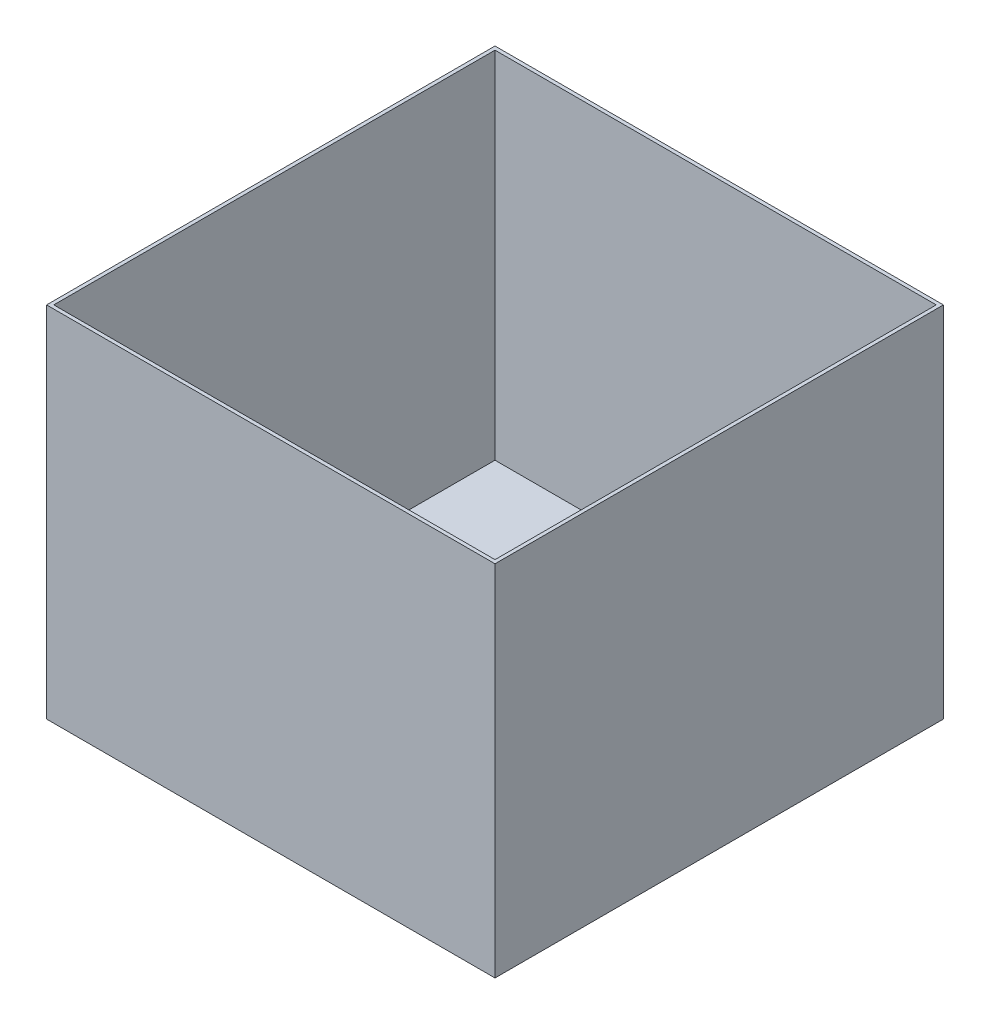
SolidWorks part; units mm, degrees
ref_plane "Front Plane" through (0, 0, 0) normal (0, 0, 1) x (1, 0, 0)
ref_plane "Top Plane" through (0, 0, 0) normal (0, 1, 0) x (1, 0, 0)
ref_plane "Right Plane" through (0, 0, 0) normal (1, 0, 0) x (0, 0, -1)
sketch "Sketch1" plane through (0, 0, 0) normal (0, 1, 0) x (1, 0, 0)
  line L1 (0, 0) -> (250, 0)
  line L2 (0, 0) -> (0, -250)
  line L3 (0, -250) -> (250, -250)
  line L4 (250, 0) -> (250, -250)
  dimension "D1" = 250
  dimension "D2" = 250
extrude "Boss-Extrude1" add sketch "Sketch1" along normal blind 200
shell "Shell1" thickness 2
ref_plane "Plane1" through (0, 0, 125) normal (0, 0, 1) x (1, 0, 0)
